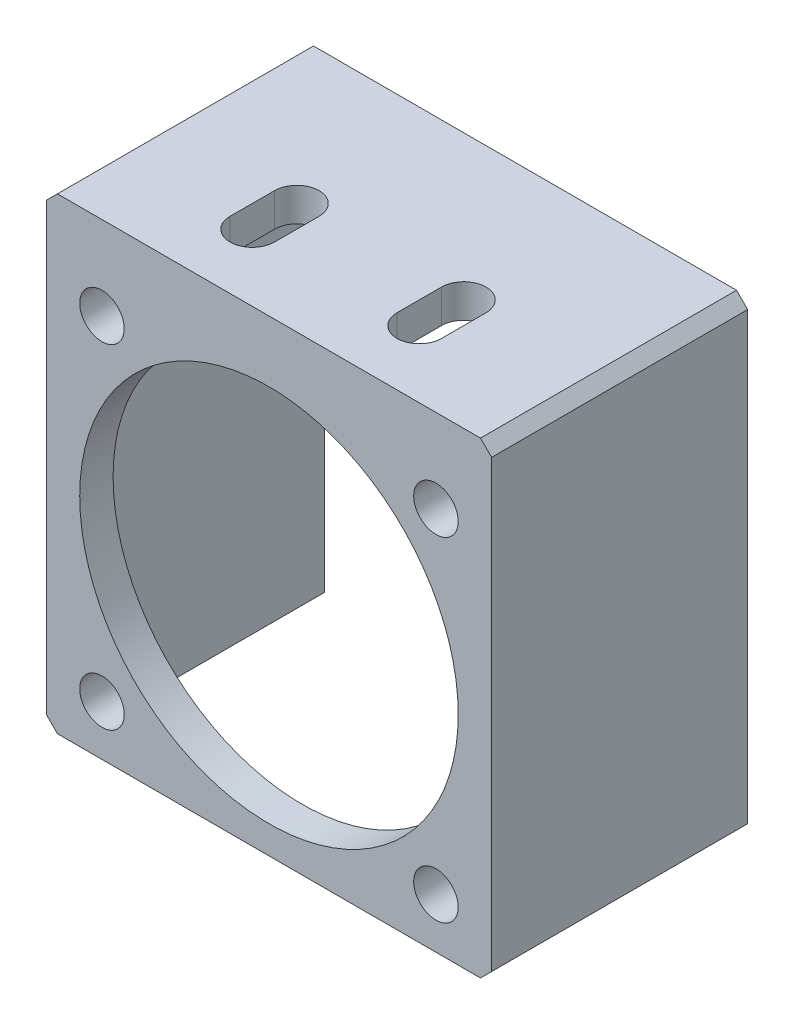
SolidWorks part; units mm, degrees
ref_plane "前视基准面" through (0, 0, 0) normal (0, 0, 1) x (1, 0, 0)
ref_plane "上视基准面" through (0, 0, 0) normal (0, 1, 0) x (1, 0, 0)
ref_plane "右视基准面" through (0, 0, 0) normal (1, 0, 0) x (0, 0, -1)
other "Configuration Table"
sketch "草图1" plane through (0, 0, 0) normal (0, 0, 1) x (1, 0, 0)
  line L8 (-46.2034, 42.3009) -> (-6.2034, 42.3009)
  line L17 (-46.2034, 0.3009) -> (-6.2034, 0.3009)
  line L21 (-46.2034, 42.3009) -> (-46.2034, 0.3009)
  line L23 (-6.2034, 42.3009) -> (-6.2034, 0.3009)
  circle A0 centre (-41.2034, 34.8009) radius 2
  circle A1 centre (-11.2034, 34.8009) radius 2
  circle A2 centre (-41.2034, 4.8009) radius 2
  circle A3 centre (-11.2034, 4.8009) radius 2
  circle A4 centre (-26.2034, 19.8009) radius 17
extrude "凸台-拉伸1" add sketch "草图1" along normal blind 3
sketch "草图2" plane through (0, 0, 0) normal (0, 0, -1) x (-1, 0, 0)
  line L0 (6.2034, 42.3009) -> (46.2034, 42.3009)
  line L2 (46.2034, 0.3009) -> (44.2034, 0.3009)
  line L3 (46.2034, 0.3009) -> (6.2034, 0.3009) construction
  line L4 (44.2034, 0.3009) -> (44.2034, 39.3009)
  line L5 (44.2034, 39.3009) -> (8.2034, 39.3009)
  line L6 (8.2034, 39.3009) -> (8.2034, 0.3009)
  line L7 (8.2034, 0.3009) -> (6.2034, 0.3009)
  line L9 (6.2034, 42.3009) -> (6.2034, 0.3009)
  line L10 (46.2034, 42.3009) -> (46.2034, 0.3009)
extrude "凸台-拉伸2" add sketch "草图2" along normal blind 20
sketch "草图3" plane through (0, 0, 3) normal (0, 0, 1) x (1, 0, 0)
  line L10 (-46.2034, 42.3009) -> (-45.2034, 42.3009)
  line L15 (-46.2034, 42.3009) -> (-6.2034, 42.3009) construction
  line L20 (-45.2034, 42.3009) -> (-46.2034, 42.3009)
  line L21 (-46.2034, 42.3009) -> (-46.2034, 41.3009)
  line L22 (-46.2034, 42.3009) -> (-46.2034, 0.3009) construction
  line L23 (-46.2034, 41.3009) -> (-45.2034, 42.3009)
  line L24 (-6.2034, 42.3009) -> (-7.2034, 42.3009)
  line L25 (-7.2034, 42.3009) -> (-6.2034, 42.3009)
  line L26 (-6.2034, 42.3009) -> (-6.2034, 41.3009)
  line L27 (-6.2034, 42.3009) -> (-6.2034, 0.3009) construction
  line L28 (-6.2034, 41.3009) -> (-7.2034, 42.3009)
  line L29 (-46.2034, 0.3009) -> (-46.2034, 1.3009)
  line L30 (-46.2034, 1.3009) -> (-46.2034, 0.3009)
  line L31 (-45.2034, 0.3009) -> (-46.2034, 1.3009)
  line L32 (-46.2034, 0.3009) -> (-6.2034, 0.3009) construction
  line L33 (-6.2034, 0.3009) -> (-6.2034, 1.3009)
  line L34 (-6.2034, 1.3009) -> (-6.2034, 0.3009)
  line L35 (-7.2034, 0.3009) -> (-6.2034, 1.3009)
extrude "切除-拉伸1" cut sketch "草图3" against normal blind 25
sketch "草图5" plane through (0, 42.3009, 0) normal (0, 1, 0) x (1, 0, 0)
  line L8 (-35.7034, 7) -> (-35.7034, 3)
  line L10 (-31.7034, 3) -> (-31.7034, 7)
  line L12 (-20.7034, 7) -> (-20.7034, 3)
  line L14 (-16.7034, 3) -> (-16.7034, 7)
  arc A0 (-35.7034, 3) -> (-31.7034, 3) centre (-33.7034, 3) ccw
  arc A1 (-20.7034, 3) -> (-16.7034, 3) centre (-18.7034, 3) ccw
  arc A2 (-31.7034, 7) -> (-35.7034, 7) centre (-33.7034, 7) ccw
  arc A3 (-16.7034, 7) -> (-20.7034, 7) centre (-18.7034, 7) ccw
extrude "切除-拉伸2" cut sketch "草图5" against normal blind 4
